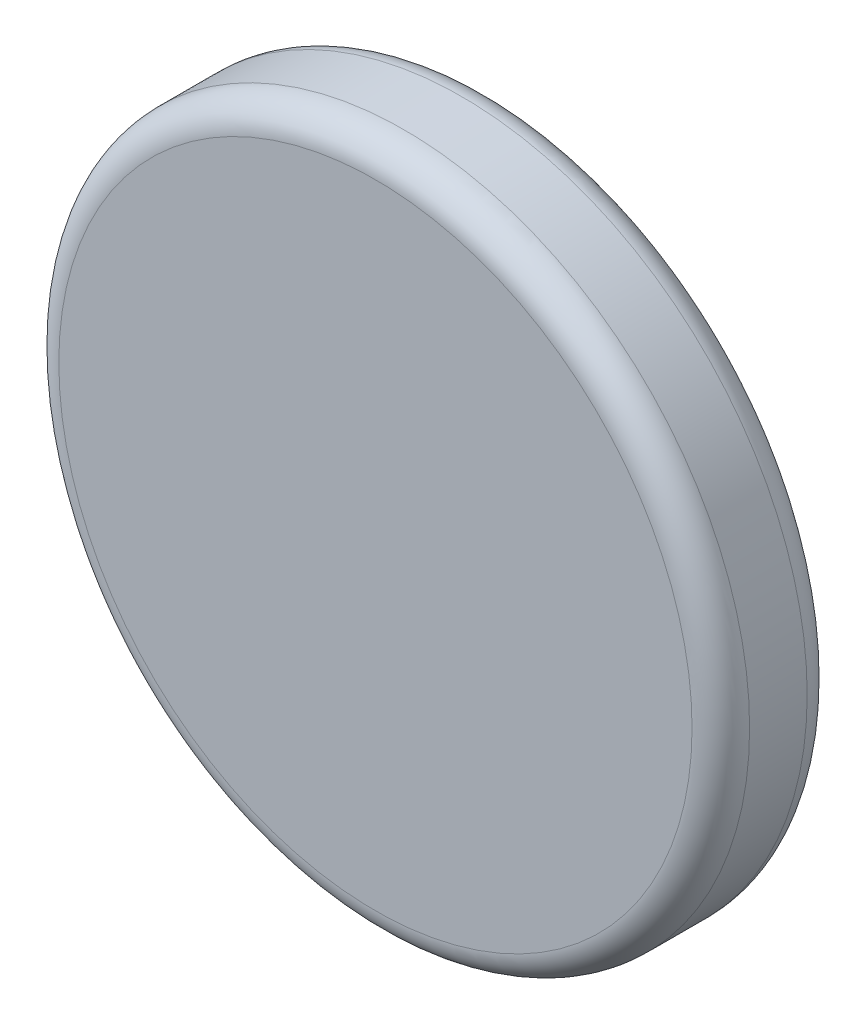
SolidWorks part; units mm, degrees
ref_plane "前视基准面" through (0, 0, 0) normal (0, 0, 1) x (1, 0, 0)
ref_plane "上视基准面" through (0, 0, 0) normal (0, 1, 0) x (1, 0, 0)
ref_plane "右视基准面" through (0, 0, 0) normal (1, 0, 0) x (0, 0, -1)
sketch "草图1" plane through (0, 0, 0) normal (0, 0, 1) x (1, 0, 0)
  circle A0 centre (0, 0) radius 120
extrude "凸台-拉伸1" add sketch "草图1" along normal blind 40
fillet "圆角1" radius 10 2 edges at (120, 0, 0) (120, 0, 40)
